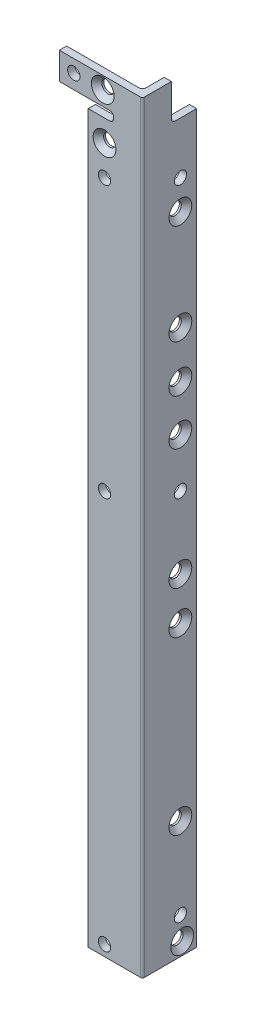
SolidWorks part; units mm, degrees
material "6061-T6 (SS)"
ref_plane "Front Plane" through (0, 0, 0) normal (0, 0, 1) x (1, 0, 0)
ref_plane "Top Plane" through (0, 0, 0) normal (0, 1, 0) x (1, 0, 0)
ref_plane "Right Plane" through (0, 0, 0) normal (1, 0, 0) x (0, 0, -1)
sketch "Sketch1" plane through (0, 0, 0) normal (0, 1, 0) x (1, 0, 0)
  line L1 (0, 0) -> (-15, 0)
  line L2 (0, 0) -> (0, 15)
  line L3 (0, 15) -> (-15, 15)
  line L4 (-15, 0) -> (-15, 15)
  line L5 (-15, 15) -> (-2, 15)
  line L6 (-15, 15) -> (-15, 2)
  line L7 (-15, 2) -> (-2, 2)
  line L8 (-2, 15) -> (-2, 2)
  dimension "D1" = 15
  dimension "D2" = 15
  dimension "D3" = 2
  dimension "D4" = 2
extrude "Boss-Extrude1" add sketch "Sketch1" along normal blind 211 contours L3 L8 L7 L4 L1 L2
sketch "Sketch2" plane through (0, 0, 0) normal (1, 0, 0) x (0, 0, -1)
  line L0 (10.5, 211) -> (37.285, 211)
  line L1 (0, 211) -> (15, 211) construction
  line L2 (15, 211) -> (15, 0) construction
  line L3 (-111.7441, 200.1035) -> (-11.7441, 200.1035)
  circle A0 centre (10.5, 32.5107) radius 1.6
  circle A1 centre (10.5, 79.9207) radius 1.6
  circle A2 centre (10.5, 103.5207) radius 1.6
  circle A3 centre (10.5, 125.1207) radius 1.6
  circle A4 centre (10.5, 137.8117) radius 1.6
  circle A5 centre (10.5, 150.8117) radius 1.6
  circle A6 centre (10.5, 178.5483) radius 1.6
  circle A7 centre (-101.2441, 21.5552) radius 1.6
  circle A8 centre (-101.2441, 58.2242) radius 1.55
  circle A9 centre (-101.2441, 81.8242) radius 1.55
  circle A10 centre (-101.2441, 114.2242) radius 1.6
  circle A11 centre (-101.2441, 126.9152) radius 1.55
  circle A12 centre (-101.2441, 139.9152) radius 1.55
  circle A13 centre (-101.2441, 167.6518) radius 1.55
  dimension "D1" = 32.4517
  dimension "D2" = 27.7366
  dimension "D3" = 13
  dimension "D4" = 12.691
  dimension "D5" = 21.6
  dimension "D6" = 23.6
  dimension "D7" = 47.41
  dimension "D8" = 26.785
  dimension "D9" = 4.5
  dimension "D10" = 27.7366
  dimension "D11" = 13
  dimension "D12" = 12.691
  dimension "D13" = 32.4
  dimension "D14" = 23.6
  dimension "D15" = 36.669
  dimension "D16" = 32.4517
hole_wizard "CSK for M3 Flat Head Machine Screw1" positions "Sketch3" profile "Sketch4" countersink size "M3" standard "ANSI Metric" end condition through all
sketch "Sketch3" plane through (0, 0, 0) normal (1, 0, 0) x (0, 0, -1)
  line L0 (15, 87.589) -> (6, 87.589) construction
  point P0 (10.5, 178.5483)
  point P3 (10.5, 150.8117)
  point P6 (10.5, 137.8117)
  point P9 (10.5, 125.1207)
  point P12 (10.5, 91.719)
  point P15 (10.5, 79.9207)
  point P18 (10.5, 32.5107)
  dimension "D1" = 4.13
sketch "Sketch4" plane through (0, 178.5483, -10.5) normal (0, 1, 0) x (0, 0, -1)
  line L0 (0, 0) -> (0, 15)
  line L1 (0, 15) -> (1.7, 15)
  line L2 (1.7, 15) -> (1.7, 1.45)
  line L3 (1.7, 1.45) -> (3.15, 0)
  line L5 (3.15, 0) -> (0, 0)
  line L6 (-1.7, 1.45) -> (-3.15, 0) construction
  line L11 (0, -6.35) -> (0, 107.95) construction
  dimension "Thru Hole Dia." = 3.4
  dimension "Thru Hole Depth" = 15
  dimension "Near C'Sink Dia." = 6.3
  dimension "Near C'Sink Angle" = 90
sketch "Sketch5" plane through (0, 0, 0) normal (1, 0, 0) x (0, 0, -1)
  line L0 (15, 211) -> (15, 0) construction
  line L1 (15, 211) -> (8, 211)
  line L2 (15, 211) -> (15, 201)
  line L3 (15, 201) -> (8, 201)
  line L4 (8, 211) -> (8, 201)
  line L5 (0, 211) -> (0, 0) construction
  line L6 (0, 211) -> (15, 211) construction
  dimension "D1" = 8
  dimension "D2" = 0
  dimension "D3" = 10
extrude "Cut-Extrude1" cut sketch "Sketch5" against normal through all
sketch "Sketch6" plane through (0, 0, 0) normal (0, 0, 1) x (1, 0, 0)
  line L0 (-15, 211) -> (-15, 0) construction
  line L1 (-15, 201) -> (-8, 201)
  line L2 (-15, 201) -> (-15, 203.5)
  line L3 (-15, 203.5) -> (-8, 203.5)
  line L4 (-8, 201) -> (-8, 203.5)
  line L5 (0, 211) -> (0, 0) construction
  dimension "D1" = 8
  dimension "D2" = 2.5
extrude "Cut-Extrude2" cut sketch "Sketch6" against normal through all
sketch "Sketch7" plane through (0, 0, 0) normal (0, 0, 1) x (1, 0, 0)
  line L0 (0, 211) -> (-15, 211) construction
  line L1 (-15, 211) -> (-15, 203.5) construction
  circle A0 centre (-11, 207.5) radius 1.3723
  dimension "D1" = 3.5
  dimension "D2" = 4
hole_wizard "CSK for M3 Flat Head Machine Screw2" positions "Sketch8" profile "Sketch9" countersink size "M3" standard "ANSI Metric" end condition through all
sketch "Sketch8" plane through (0, 0, 0) normal (0, 0, 1) x (1, 0, 0)
  line L0 (-15, 201) -> (-15, 0) construction
  line L1 (0, 211) -> (-15, 211) construction
  point P0 (-11, 207.5)
  point P3 (-10.5, 195)
  dimension "D1" = 4.5
  dimension "D2" = 16
sketch "Sketch9" plane through (-11, 207.5, 0) normal (1, 0, 0) x (0, -1, 0)
  line L0 (0, 0) -> (0, 15)
  line L1 (0, 15) -> (1.7, 15)
  line L2 (1.7, 15) -> (1.7, 1.45)
  line L3 (1.7, 1.45) -> (3.15, 0)
  line L5 (3.15, 0) -> (0, 0)
  line L6 (-1.7, 1.45) -> (-3.15, 0) construction
  line L11 (0, -6.35) -> (0, 107.95) construction
  dimension "Thru Hole Dia." = 3.4
  dimension "Thru Hole Depth" = 15
  dimension "Near C'Sink Dia." = 6.3
  dimension "Near C'Sink Angle" = 90
sketch "Sketch10" plane through (0, 0, 0) normal (1, 0, 0) x (0, 0, -1)
  line L0 (15, 201) -> (15, 0) construction
  line L1 (0, 0) -> (15, 0) construction
  circle A0 centre (11, 3.5) radius 1.8562
  dimension "D1" = 4
  dimension "D2" = 3.5
hole_wizard "CSK for M3 Flat Head Machine Screw3" positions "Sketch11" profile "Sketch12" countersink size "M3" standard "ANSI Metric" end condition through all
sketch "Sketch11" plane through (0, 0, 0) normal (1, 0, 0) x (0, 0, -1)
  point P0 (11, 3.5)
sketch "Sketch12" plane through (0, 3.5, -11) normal (0, 1, 0) x (0, 0, -1)
  line L0 (0, 0) -> (0, 15)
  line L1 (0, 15) -> (1.7, 15)
  line L2 (1.7, 15) -> (1.7, 1.45)
  line L3 (1.7, 1.45) -> (3.15, 0)
  line L5 (3.15, 0) -> (0, 0)
  line L6 (-1.7, 1.45) -> (-3.15, 0) construction
  line L11 (0, -6.35) -> (0, 107.95) construction
  dimension "Thru Hole Dia." = 3.4
  dimension "Thru Hole Depth" = 15
  dimension "Near C'Sink Dia." = 6.3
  dimension "Near C'Sink Angle" = 90
fillet "Fillet1" radius 0.5 1 edges at (0, 105.5, 0)
fillet "Fillet2" radius 1 4 edges at (-8, 203.5, -1) (-8, 201, -1) (-2, 105.5, -2) (-1, 201, -8)
sketch "Sketch13" plane through (0, 0, 0) normal (1, 0, 0) x (0, 0, -1)
  line L0 (0.5, 0) -> (15, 0) construction
  circle A4 centre (10.5, 10) radius 1.7
  circle A5 centre (10.5, 111.59) radius 1.7
  circle A6 centre (10.5, 186.68) radius 1.7
  circle A7 centre (10.5, 178.5483) radius 1.7 construction
  circle A8 centre (10.5, 178.5483) radius 1.7
  dimension "D1" = 186.68
  dimension "D2" = 111.59
  dimension "D3" = 10
extrude "Cut-Extrude3" cut sketch "Sketch13" against normal blind 10
sketch "Sketch14" plane through (0, 0, 0) normal (0, 0, 1) x (1, 0, 0)
  line L0 (-0.5, 0) -> (-15, 0) construction
  circle A0 centre (-10.5, 195) radius 1.7 construction
  circle A1 centre (-10.5, 195) radius 1.7
  circle A2 centre (-10.5, 186.68) radius 1.7
  circle A3 centre (-10.5, 111.59) radius 1.7
  circle A4 centre (-10.5, 3) radius 1.7
  dimension "D1" = 3
  dimension "D2" = 111.59
  dimension "D3" = 186.68
extrude "Cut-Extrude4" cut sketch "Sketch14" against normal blind 10
sketch "Sketch16" plane through (-15, 0, 0) normal (-1, 0, 0) x (0, 0, 1)
  line L1 (-2, 211) -> (0, 211)
  line L2 (-2, 211) -> (-2, 203.5)
  line L3 (-2, 203.5) -> (0, 203.5)
  line L4 (0, 211) -> (0, 203.5)
  dimension "D1" = 7.5
  dimension "D2" = 2
extrude "Boss-Extrude2" add sketch "Sketch16" along normal blind 8
sketch "Sketch17" plane through (0, 0, -2) normal (0, 0, -1) x (-1, 0, 0)
  line L0 (23, 211) -> (23, 203.5) construction
  line L1 (23, 211) -> (3, 211) construction
  circle A0 centre (19, 207.5) radius 1.7
  dimension "D1" = 4
  dimension "D2" = 3.5
extrude "Cut-Extrude5" cut sketch "Sketch17" against normal blind 8
